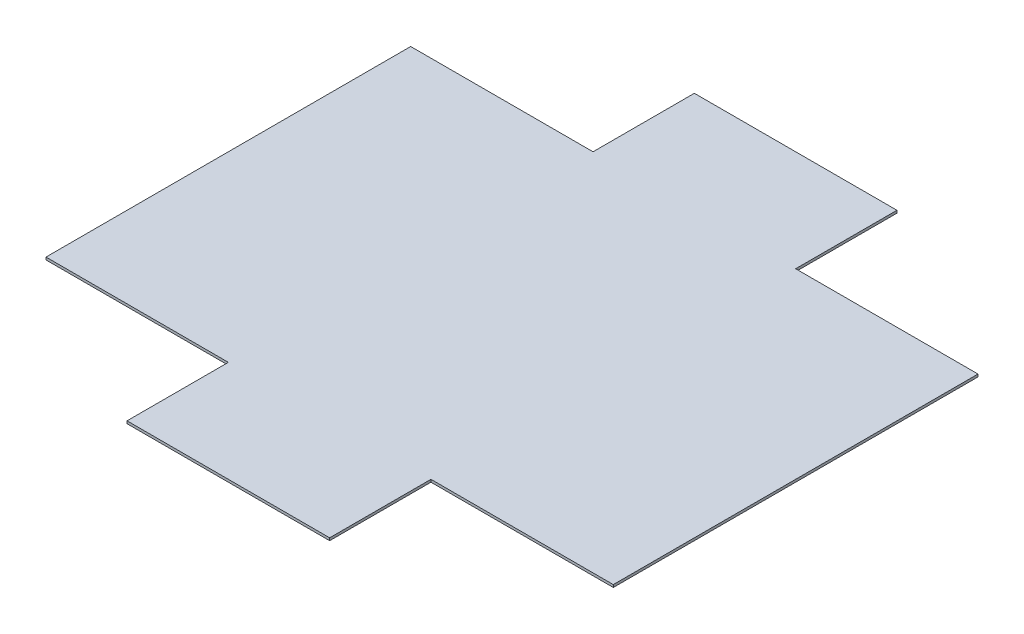
SolidWorks part; units mm, degrees
material "1060 Alloy"
ref_plane "Front Plane" through (0, 0, 0) normal (0, 0, 1) x (1, 0, 0)
ref_plane "Top Plane" through (0, 0, 0) normal (0, 1, 0) x (1, 0, 0)
ref_plane "Right Plane" through (0, 0, 0) normal (1, 0, 0) x (0, 0, -1)
sketch "Sketch1" plane through (0, 0, 0) normal (0, 1, 0) x (1, 0, 0)
  line L0 (0, 584.2) -> (228.6, 584.2)
  line L1 (228.6, 0) -> (482.6, 0)
  line L2 (0, 127) -> (0, 584.2)
  line L3 (228.6, 711.2) -> (482.6, 711.2)
  line L4 (711.2, 127) -> (711.2, 584.2)
  line L5 (228.6, 584.2) -> (228.6, 711.2)
  line L6 (482.6, 711.2) -> (482.6, 584.2)
  line L7 (482.6, 584.2) -> (711.2, 584.2)
  line L8 (0, 127) -> (228.6, 127)
  line L9 (228.6, 127) -> (228.6, 0)
  line L10 (711.2, 127) -> (482.6, 127)
  line L11 (482.6, 127) -> (482.6, 0)
  dimension "D1" = 711.2
  dimension "D2" = 711.2
  dimension "D3" = 228.6
  dimension "D4" = 127
  dimension "D5" = 228.6
  dimension "D6" = 127
  dimension "D7" = 228.6
  dimension "D8" = 127
  dimension "D9" = 228.6
extrude "Boss-Extrude1" add sketch "Sketch1" along normal blind 3.175
